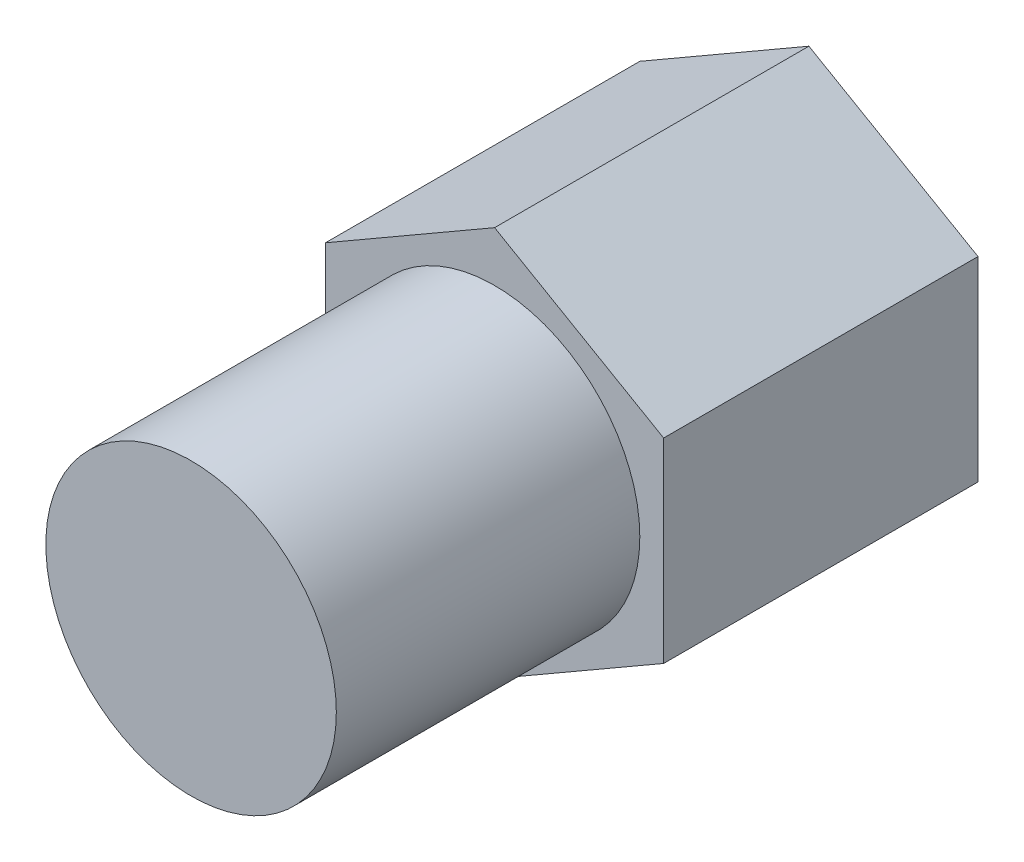
SolidWorks part; units mm, degrees
ref_plane "Front Plane" through (0, 0, 0) normal (1, 0, 0) x (0, 1, 0)
ref_plane "Top Plane" through (0, 0, 0) normal (0, 0, 1) x (0, 1, 0)
ref_plane "Right Plane" through (0, 0, 0) normal (0, 1, 0) x (-1, 0, 0)
sketch "Sketch1" plane through (0, 0, 0) normal (0, 0, 1) x (0, 1, 0)
  line L1 (9.0067, 0) -> (4.5033, 7.8)
  line L2 (4.5033, 7.8) -> (-4.5033, 7.8)
  line L3 (-4.5033, 7.8) -> (-9.0067, 0)
  line L4 (-9.0067, 0) -> (-4.5033, -7.8)
  line L5 (-4.5033, -7.8) -> (4.5033, -7.8)
  line L6 (4.5033, -7.8) -> (9.0067, 0)
  circle A0 centre (0, 0) radius 7.8 construction
  dimension "D1" = 15.6
extrude "Boss-Extrude1" add sketch "Sketch1" along normal blind 14.5
sketch "Sketch2" plane through (0, 0, 14.5) normal (0, 0, 1) x (1, 0, 0)
  circle A0 centre (0, 0) radius 6.7
  dimension "D1" = 13.4
extrude "Boss-Extrude2" add sketch "Sketch2" along normal blind 14
